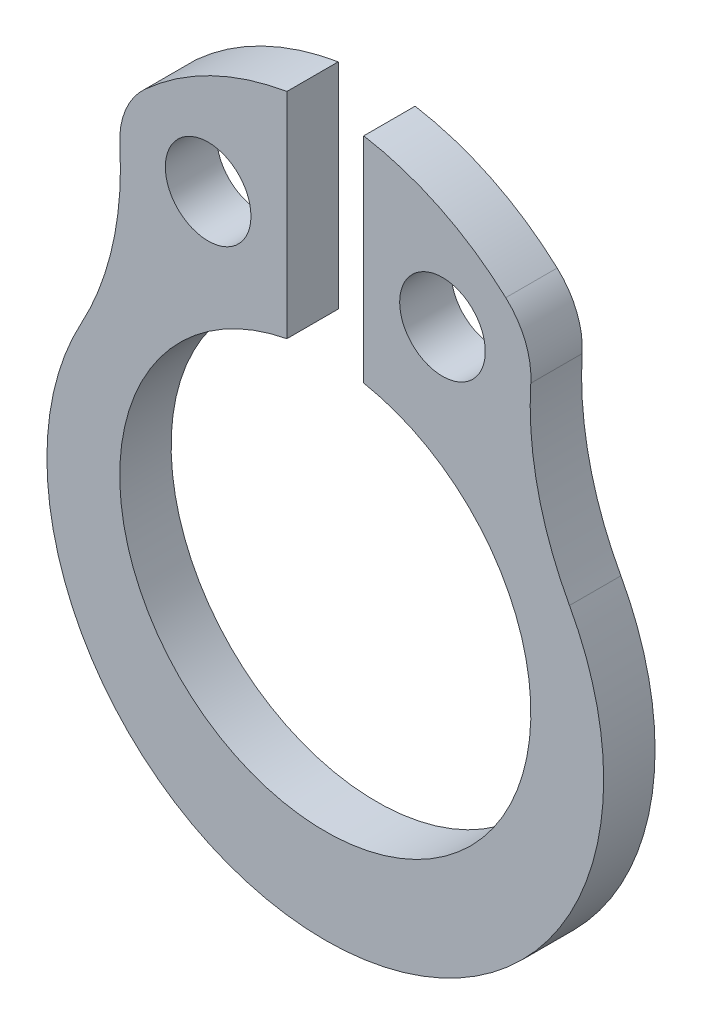
SolidWorks part; units mm, degrees
ref_plane "Front Plane" through (0, 0, 0) normal (0, 0, 1) x (1, 0, 0)
ref_plane "Top Plane" through (0, 0, 0) normal (0, 1, 0) x (1, 0, 0)
ref_plane "Right Plane" through (0, 0, 0) normal (1, 0, 0) x (0, 0, -1)
sketch "Sketch1" plane through (0, 0, 0) normal (0, 0, 1) x (1, 0, 0)
  line L0 (0, -1000) -> (0, 49000) construction
  line L1 (-1000, 0) -> (49000, 0) construction
  line L2 (0.4486, 4.8577) -> (0.4486, 2.3577)
  line L3 (0, 4.8577) -> (0.4486, 4.8577) construction
  line L4 (-0.4486, 4.8577) -> (-0.4486, 2.3577)
  circle A0 centre (0, 0) radius 2.4 construction
  circle A1 centre (0, 0) radius 3.5 construction
  circle A5 centre (0, -0.25) radius 3.25 construction
  arc A6 (-2.8509, 1.3105) -> (2.8509, 1.3105) centre (0, -0.25) ccw
  circle A8 centre (-1.368, 3.386) radius 0.5
  circle A12 centre (1.368, 3.386) radius 0.5
  arc A13 (-0.4486, 4.8577) -> (-2.107, 4.0507) centre (0.093, 1.6372) ccw
  arc A14 (-2.107, 4.0507) -> (-2.3988, 3.3314) centre (-1.5011, 3.386) ccw
  arc A15 (-2.3988, 3.3314) -> (-2.8509, 1.3105) centre (-6.1286, 3.1047) cw
  arc A16 (2.3988, 3.3314) -> (2.8509, 1.3105) centre (6.1286, 3.1047) ccw
  arc A17 (2.107, 4.0507) -> (2.3988, 3.3314) centre (1.5011, 3.386) cw
  arc A18 (0.4486, 4.8577) -> (2.107, 4.0507) centre (-0.093, 1.6372) cw
  arc A19 (-0.4486, 2.3577) -> (0.4486, 2.3577) centre (0, 0) ccw
  point P5 (0, -2.4)
  point P6 (0, -3.5)
  point P19 (0, 4.8577)
  dimension "D1" = 4.8
  dimension "D2" = 0.25
  dimension "D3" = 1.1
  dimension "D4" = 2.5
extrude "Boss-Extrude1" add sketch "Sketch1" along normal mid plane 0.6
